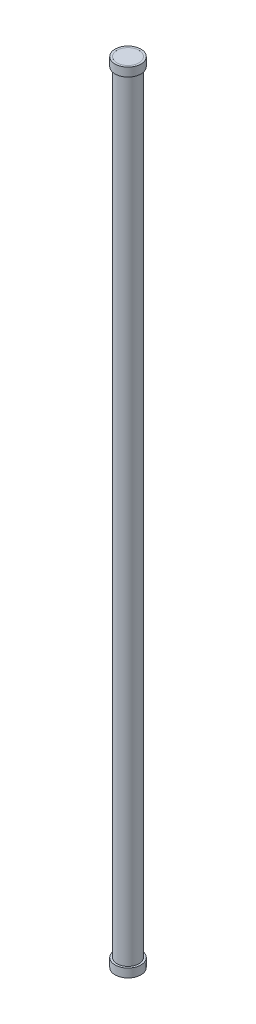
SolidWorks part; units mm, degrees
ref_plane "Alzado" through (0, 0, 0) normal (0, 0, 1) x (1, 0, 0)
ref_plane "Planta" through (0, 0, 0) normal (0, 1, 0) x (1, 0, 0)
ref_plane "Vista lateral" through (0, 0, 0) normal (1, 0, 0) x (0, 0, -1)
sketch "Croquis1" plane through (0, 0, 0) normal (0, 1, 0) x (1, 0, 0)
  circle A0 centre (0, 0) radius 12.7
extrude "Saliente-Extruir1" add sketch "Croquis1" along normal blind 915
sketch "Croquis2" plane through (0, 915, 0) normal (0, 1, 0) x (1, 0, 0)
  circle A0 centre (0, 0) radius 15
  circle A1 centre (0, 0) radius 12.7
extrude "Saliente-Extruir2" add sketch "Croquis2" against normal blind 10 separate body
sketch "Croquis3" plane through (0, 0, 0) normal (0, -1, 0) x (1, 0, 0)
  circle A0 centre (0, 0) radius 15
  circle A1 centre (0, 0) radius 12.7
extrude "Saliente-Extruir3" add sketch "Croquis3" against normal blind 10
